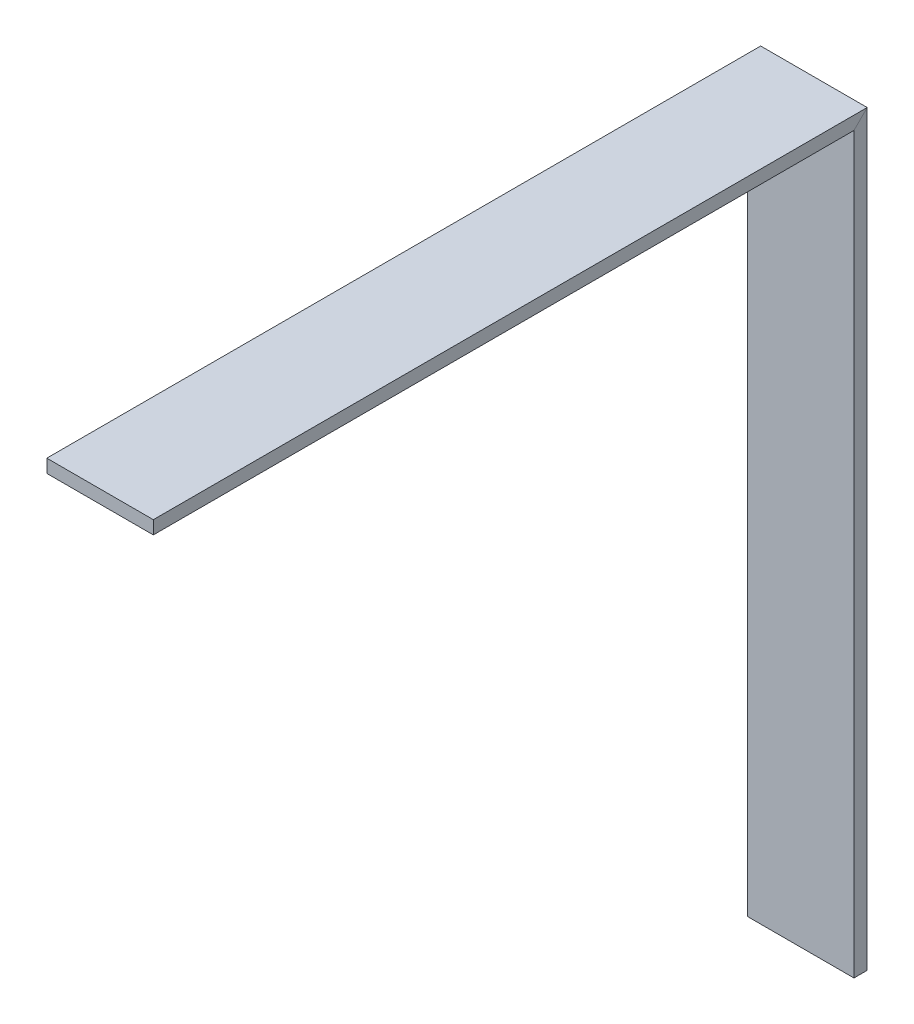
SolidWorks part; units mm, degrees
ref_plane "Alzado" through (0, 0, 0) normal (0, 0, 1) x (1, 0, 0)
ref_plane "Planta" through (0, 0, 0) normal (0, 1, 0) x (1, 0, 0)
ref_plane "Vista lateral" through (0, 0, 0) normal (1, 0, 0) x (0, 0, -1)
sketch "Croquis1" plane through (0, 0, 0) normal (0, 0, 1) x (1, 0, 0)
  line L1 (-25.4, 3.155) -> (25.4, 3.155)
  line L2 (-25.4, 3.155) -> (-25.4, -3.155)
  line L3 (-25.4, -3.155) -> (25.4, -3.155)
  line L4 (25.4, 3.155) -> (25.4, -3.155)
  line L5 (-25.4, 3.155) -> (25.4, -3.155) construction
  line L6 (-25.4, -3.155) -> (25.4, 3.155) construction
  point P0 (0, 0)
  dimension "D1" = 50.8
  dimension "D2" = 6.31
extrude "Saliente-Extruir1" add sketch "Croquis1" along normal blind 574
sketch "Croquis2" plane through (0, 3.155, 0) normal (0, 1, 0) x (1, 0, 0)
  line L0 (25.4, -574) -> (25.4, 0) construction
  line L1 (-25.4, 0) -> (25.4, 0)
  line L2 (-25.4, 0) -> (-25.4, -6.31)
  line L3 (-25.4, -6.31) -> (25.4, -6.31)
  line L4 (25.4, 0) -> (25.4, -6.31)
  line L5 (-25.4, 0) -> (25.4, -6.31) construction
  line L6 (-25.4, -6.31) -> (25.4, 0) construction
  line L7 (-25.4, -574) -> (-25.4, 0) construction
  point P0 (0, -3.155)
  dimension "D1" = 6.31
extrude "Saliente-Extruir2" add sketch "Croquis2" against normal blind 716
sketch "Croquis3" plane through (0, -3.155, 0) normal (0, -1, 0) x (1, 0, 0)
  line L1 (25.4, 567.69) -> (-25.4, 567.69)
  line L2 (25.4, 567.69) -> (25.4, 574)
  line L3 (25.4, 574) -> (-25.4, 574)
  line L4 (-25.4, 567.69) -> (-25.4, 574)
  line L5 (25.4, 567.69) -> (-25.4, 574) construction
  line L6 (25.4, 574) -> (-25.4, 567.69) construction
  point P0 (0, 570.845)
  dimension "D1" = 6.31
sketch "Croquis4" plane through (0, 0, 6.31) normal (0, 0, 1) x (1, 0, 0)
  line L1 (25.4, -706.535) -> (-25.4, -706.535)
  line L2 (25.4, -706.535) -> (25.4, -712.845)
  line L3 (25.4, -712.845) -> (-25.4, -712.845)
  line L4 (-25.4, -706.535) -> (-25.4, -712.845)
  line L5 (25.4, -706.535) -> (-25.4, -712.845) construction
  line L6 (25.4, -712.845) -> (-25.4, -706.535) construction
  point P0 (0, -709.69)
  dimension "D1" = 6.31
  dimension "D2" = 50.8
sketch "Croquis5" plane through (25.4, 0, 0) normal (1, 0, 0) x (0, 0, -1)
  line L0 (-612.0924, 61.3408) -> (-612.0924, -272.0779)
  line L1 (-612.0924, -272.0779) -> (102.3762, -272.0779)
  line L2 (102.3762, -272.0779) -> (102.3762, 61.3408)
  line L3 (102.3762, 61.3408) -> (-612.0924, 61.3408)
extrude "Cortar-Extruir1" cut sketch "Croquis5" against normal blind 122
sketch "Croquis6" plane through (0, 0, 6.31) normal (0, 0, 1) x (1, 0, 0)
  line L1 (-25.4, -278.3879) -> (25.4, -278.3879)
  line L2 (-25.4, -278.3879) -> (-25.4, -272.0779)
  line L3 (-25.4, -272.0779) -> (25.4, -272.0779)
  line L4 (25.4, -278.3879) -> (25.4, -272.0779)
  line L5 (-25.4, -278.3879) -> (25.4, -272.0779) construction
  line L6 (-25.4, -272.0779) -> (25.4, -278.3879) construction
  point P0 (0, -275.2329)
  dimension "D1" = 6.31
sketch3d "Croquis3D1"
  line L0 (0, -275.2329, 6.31) -> (0, -275.2329, 3.159)
  line L1 (0, -275.2329, 3.159) -> (0, 149.1071, 3.159)
  line L2 (0, 149.1071, 3.159) -> (0, 149.1071, 340.399)
  dimension "D1" = 424.34
  dimension "D3" = 337.24
sweep "Barrer1" add profiles "Croquis6" path "Croquis3D1"
sketch "Croquis8" plane through (0, 145.9521, 0) normal (0, -1, 0) x (-1, 0, 0)
  line L0 (0, -3.159) -> (0, -340.399) construction
  circle A0 centre (0, -715.8782) radius 5.4507
extrude "Saliente-Extruir3" add sketch "Croquis4" against normal blind 603.01
sketch "Croquis11" plane through (0, -706.535, 0) normal (0, 1, 0) x (1, 0, 0)
  circle A0 centre (0, 324.2932) radius 5.7526
sketch "Croquis13" plane through (0, -706.535, 0) normal (0, 1, 0) x (1, 0, 0)
  circle A0 centre (0, 460.3922) radius 4.75
sketch "Croquis14" plane through (25.4, 0, 0) normal (1, 0, 0) x (0, 0, -1)
  line L0 (-6.3114, -204.0479) -> (-0.004, -204.0479)
  line L1 (-6.3109, -272.0787) -> (-6.314, 145.9521) construction
  line L2 (-0.004, -272.0779) -> (-0.004, 152.2621) construction
  line L4 (2.7906, -706.535) -> (596.7, -706.535)
  line L5 (596.7, -706.535) -> (596.7, -712.845)
  line L6 (596.7, -712.845) -> (-6.31, -712.845)
  line L7 (2.7906, -706.535) -> (2.7906, -204.0479)
  line L8 (-6.314, 145.9521) -> (-340.399, 145.9521) construction
  line L9 (-6.3114, -204.0479) -> (-14.9054, -204.0479)
  line L10 (-14.9054, -204.0479) -> (-14.9054, -712.845)
  line L11 (-14.9054, -712.845) -> (-6.31, -712.845)
  line L12 (2.7906, -204.0479) -> (-0.004, -204.0479)
  dimension "D1" = 350
extrude "Cortar-Extruir2" cut sketch "Croquis14" against normal blind 60
